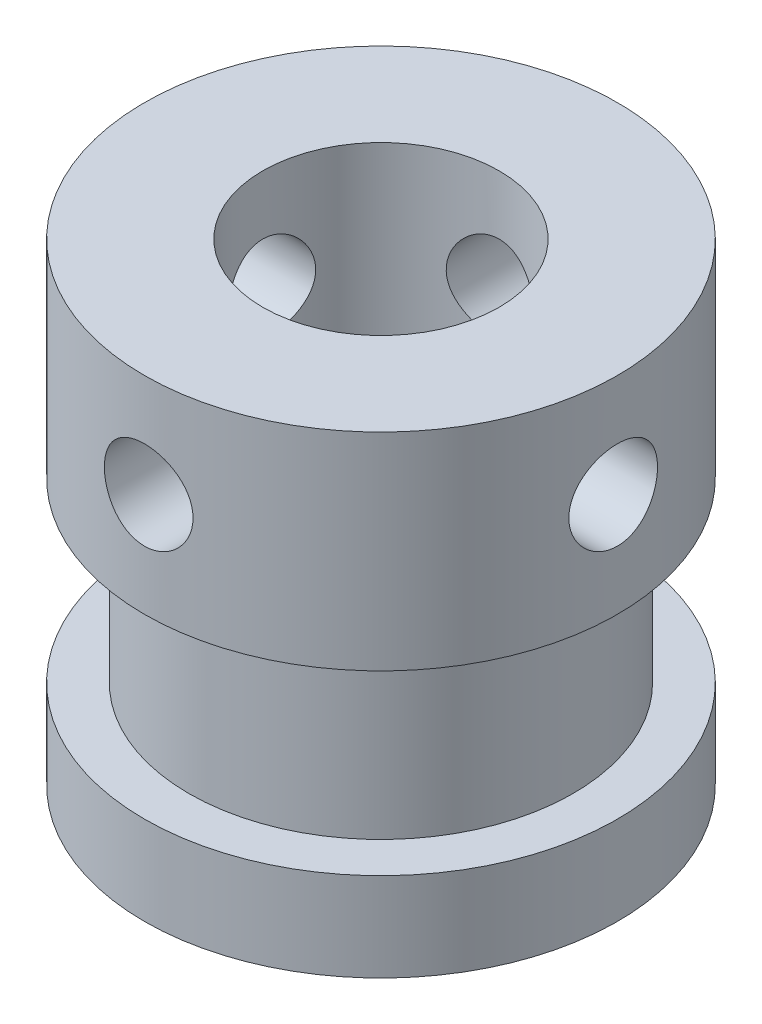
SolidWorks part; units mm, degrees
ref_plane "前视基准面" through (0, 0, 0) normal (0, 0, 1) x (1, 0, 0)
ref_plane "上视基准面" through (0, 0, 0) normal (0, 1, 0) x (1, 0, 0)
ref_plane "右视基准面" through (0, 0, 0) normal (1, 0, 0) x (0, 0, -1)
other "Configuration Table"
sketch "草图1" plane through (0, 0, 0) normal (0, 1, 0) x (1, 0, 0)
  circle A0 centre (0, 0) radius 8
  dimension "D1" = 16
extrude "凸台-拉伸1" add sketch "草图1" along normal blind 16
sketch "草图2" plane through (0, 16, 0) normal (0, 1, 0) x (1, 0, 0)
  circle A0 centre (0, 0) radius 4
  dimension "D1" = 8
extrude "切除-拉伸1" cut sketch "草图2" against normal through all
ref_plane "基准面1" through (0, 3, 0) normal (0, 1, 0) x (1, 0, 0)
sketch "草图3" plane through (0, 3, 0) normal (0, 1, 0) x (1, 0, 0)
  circle A0 centre (0, 0) radius 6.5
  dimension "D1" = 13
extrude "切除-拉伸2" cut sketch "草图3" along normal blind 6 flip side to cut
cosmetic thread "装饰螺纹线1" parameters "D1"=6, "D2"=12
sketch "草图4" plane through (0, 0, 0) normal (1, 0, 0) x (0, 0, -1)
  line L0 (0, 8.8) -> (0, -8.8) construction
  line L1 (4, 16) -> (-4, 16) construction
  circle A0 centre (0, 12.5) radius 1.5
  dimension "D1" = 3
  dimension "D2" = 3.5
extrude "切除-拉伸3" cut sketch "草图4" against normal through all and the other way through all
sketch "草图5" plane through (0, 0, 0) normal (0, 0, 1) x (1, 0, 0)
  line L0 (0, -8.8) -> (0, 8.8) construction
  line L1 (8, 16) -> (-8, 16) construction
  circle A0 centre (0, 12.5) radius 1.5
  dimension "D1" = 3
  dimension "D2" = 3.5
extrude "切除-拉伸4" cut sketch "草图5" against normal through all and the other way through all
